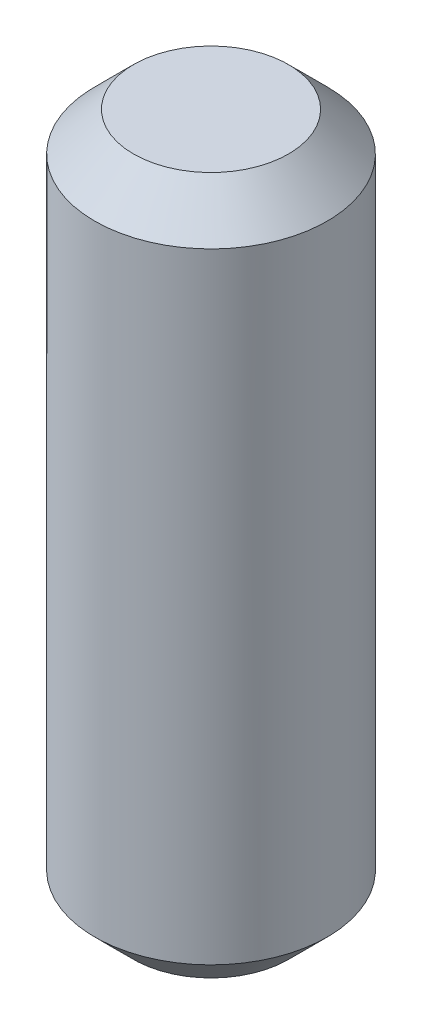
SolidWorks part; units mm, degrees
ref_plane "Front Plane" through (0, 0, 0) normal (0, 0, 1) x (1, 0, 0)
ref_plane "Top Plane" through (0, 0, 0) normal (0, 1, 0) x (1, 0, 0)
ref_plane "Right Plane" through (0, 0, 0) normal (1, 0, 0) x (0, 0, -1)
sketch "Sketch1" plane through (0, 0, 0) normal (0, 0, 1) x (1, 0, 0)
  line L0 (0, 0) -> (0, 9) construction
  line L1 (0, 9) -> (1.5, 9)
  line L2 (1.5, 9) -> (1.5, 0)
  line L3 (1.5, 0) -> (0, 0)
  line L4 (0, 0) -> (0, 9)
  dimension "D1" = 9
  dimension "D2" = 3
revolve "Revolve1" add sketch "Sketch1" angle 360 about L0
chamfer "Chamfer1" distance 0.5 angle 45 2 edges at (0, 0, -1.5) (0, 9, -1.5)
